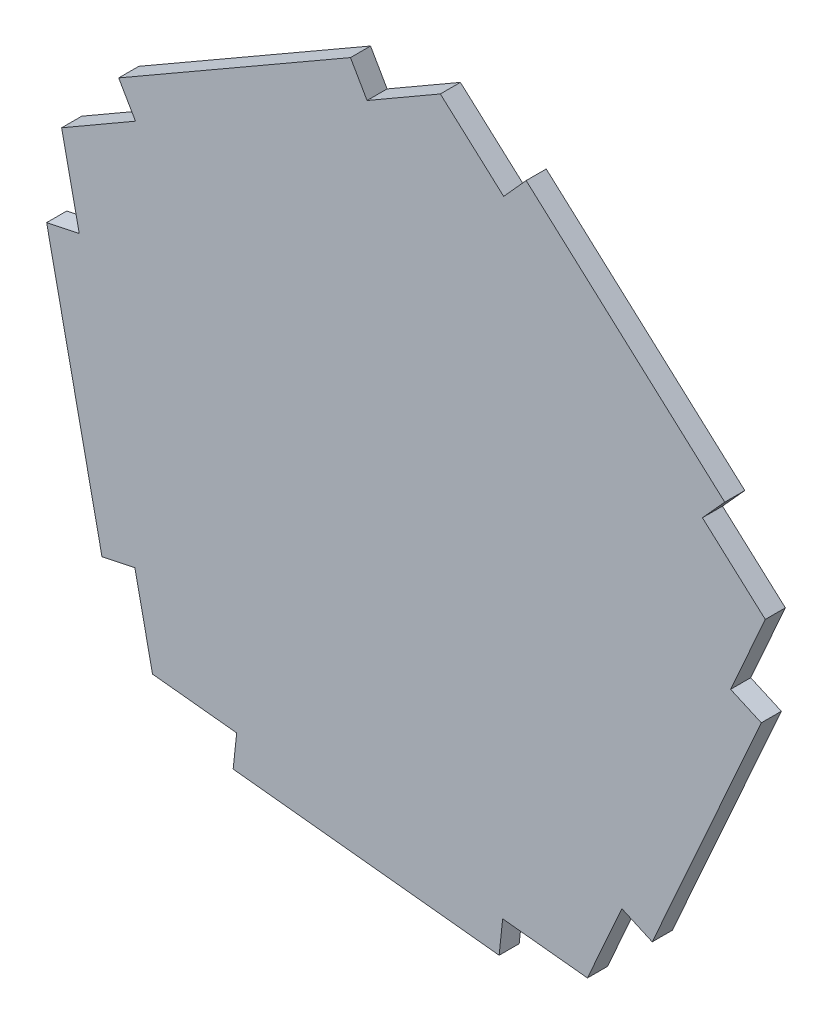
SolidWorks part; units mm, degrees
ref_plane "Front Plane" through (0, 0, 0) normal (0, 0, 1) x (1, 0, 0)
ref_plane "Top Plane" through (0, 0, 0) normal (0, 1, 0) x (1, 0, 0)
ref_plane "Right Plane" through (0, 0, 0) normal (1, 0, 0) x (0, 0, -1)
sketch "Sketch1" plane through (0, 0, 0) normal (0, 0, 1) x (1, 0, 0)
  line L1 (-41.404, -45.8843) -> (30.844, -53.5566)
  line L2 (30.844, -53.5566) -> (60.4667, 12.7845)
  line L3 (60.4667, 12.7845) -> (6.5264, 61.4578)
  line L4 (6.5264, 61.4578) -> (-56.4331, 25.1985)
  line L5 (-56.4331, 25.1985) -> (-41.404, -45.8843)
  circle A0 centre (0, 0) radius 50 construction
extrude "Boss-Extrude1" add sketch "Sketch1" along normal blind 3 contours L4 L5 L1 L2 L3
sketch "Sketch4" plane through (0, 0, 3) normal (0, 0, 1) x (1, 0, 0)
  line L0 (0, 0) -> (30.844, -53.5566) construction
  line L1 (0, 0) -> (-5.28, -49.7204) construction
  line L2 (-41.404, -45.8843) -> (30.844, -53.5566) construction
  line L3 (0, 0) -> (-41.404, -45.8843) construction
  line L4 (0, 0) -> (-48.9186, -10.3429) construction
  line L5 (0, 0) -> (-56.4331, 25.1985) construction
  line L6 (0, 0) -> (-24.9533, 43.3282) construction
  line L7 (0, 0) -> (6.5264, 61.4578) construction
  line L8 (0, 0) -> (33.4965, 37.1212) construction
  line L9 (0, 0) -> (60.4667, 12.7845) construction
  line L10 (0, 0) -> (45.6553, -20.386) construction
  line L11 (-5.28, -49.7204) -> (14.6082, -51.8324) construction
  line L12 (27.8115, -48.171) -> (54.4076, 11.5647)
  line L13 (54.4076, 11.5647) -> (5.8142, 55.3184)
  line L14 (5.8142, 55.3184) -> (-50.8142, 22.6239)
  line L15 (-50.8142, 22.6239) -> (-37.2191, -41.336)
  line L16 (-37.2191, -41.336) -> (27.8115, -48.171)
  line L17 (24.7214, -42.8187) -> (48.3623, 10.2797)
  line L18 (48.3623, 10.2797) -> (5.1682, 49.1719)
  line L19 (5.1682, 49.1719) -> (-45.1682, 20.1102)
  line L20 (-45.1682, 20.1102) -> (-33.0836, -36.7431)
  line L21 (-33.0836, -36.7431) -> (24.7214, -42.8187)
  line L22 (-41.404, -45.8843) -> (30.844, -53.5566) construction
  line L23 (14.6082, -51.8324) -> (15.1331, -46.8384)
  line L24 (15.1331, -46.8384) -> (27.8115, -48.171)
  line L25 (37.5009, -38.6482) -> (32.9179, -36.5959)
  line L26 (37.5009, -38.6482) -> (30.844, -53.5566)
  line L27 (30.844, -53.5566) -> (14.6082, -51.8324)
  line L28 (-44.7814, -29.9103) -> (-39.8696, -28.8663)
  line L29 (-25.1682, -47.6084) -> (-24.6325, -42.6156)
  line L30 (-25.1682, -47.6084) -> (-41.404, -45.8843)
  line L31 (-41.404, -45.8843) -> (-44.7814, -29.9103)
  line L32 (-39.8696, -28.8663) -> (-37.2191, -41.336)
  line L33 (-42.2846, 33.3468) -> (-39.7738, 28.9981)
  line L34 (-53.0557, 9.2245) -> (-48.1417, 10.258)
  line L35 (-53.0557, 9.2245) -> (-56.4331, 25.1985)
  line L36 (-56.4331, 25.1985) -> (-42.2846, 33.3468)
  line L37 (-39.7738, 28.9981) -> (-50.8142, 22.6239)
  line L38 (18.6481, 50.5198) -> (15.288, 46.7881)
  line L39 (-7.6221, 53.3095) -> (-5.1207, 48.9553)
  line L40 (-7.6221, 53.3095) -> (6.5264, 61.4578)
  line L41 (6.5264, 61.4578) -> (18.6481, 50.5198)
  line L42 (15.288, 46.7881) -> (5.8142, 55.3184)
  line L43 (53.8097, -2.1239) -> (49.2224, -0.0815)
  line L44 (48.345, 23.7226) -> (44.9769, 19.9981)
  line L45 (48.345, 23.7226) -> (60.4667, 12.7845)
  line L46 (60.4667, 12.7845) -> (53.8097, -2.1239)
  line L47 (49.2224, -0.0815) -> (54.4076, 11.5647)
  line L48 (32.9179, -36.5959) -> (27.8115, -48.171)
  line L49 (-39.8696, -28.8663) -> (-37.2191, -41.336)
  line L50 (-44.7814, -29.9103) -> (-39.8696, -28.8663)
  line L51 (-41.404, -45.8843) -> (-44.7814, -29.9103)
  line L52 (-25.1682, -47.6084) -> (-41.404, -45.8843)
  line L53 (-25.1682, -47.6084) -> (-24.6325, -42.6156)
  line L54 (-24.6325, -42.6156) -> (-37.2191, -41.336)
  line L55 (-39.7738, 28.9981) -> (-50.8142, 22.6239)
  line L56 (-42.2846, 33.3468) -> (-39.7738, 28.9981)
  line L57 (-56.4331, 25.1985) -> (-42.2846, 33.3468)
  line L58 (-53.0557, 9.2245) -> (-56.4331, 25.1985)
  line L59 (-53.0557, 9.2245) -> (-48.1417, 10.258)
  line L60 (-48.1417, 10.258) -> (-50.8142, 22.6239)
  line L61 (15.288, 46.7881) -> (5.8142, 55.3184)
  line L62 (18.6481, 50.5198) -> (15.288, 46.7881)
  line L63 (6.5264, 61.4578) -> (18.6481, 50.5198)
  line L64 (-7.6221, 53.3095) -> (6.5264, 61.4578)
  line L65 (-7.6221, 53.3095) -> (-5.1207, 48.9553)
  line L66 (-5.1207, 48.9553) -> (5.8142, 55.3184)
  line L67 (49.2224, -0.0815) -> (54.4076, 11.5647)
  line L68 (53.8097, -2.1239) -> (49.2224, -0.0815)
  line L69 (60.4667, 12.7845) -> (53.8097, -2.1239)
  line L70 (48.345, 23.7226) -> (60.4667, 12.7845)
  line L71 (48.345, 23.7226) -> (44.9769, 19.9981)
  line L72 (44.9769, 19.9981) -> (54.4076, 11.5647)
  circle A0 centre (0, 0) radius 45 construction
  circle A1 centre (0, 0) radius 40 construction
  circle A2 centre (0, 0) radius 45 construction
  circle A3 centre (0, 0) radius 45 construction
  circle A4 centre (0, 0) radius 45 construction
  circle A5 centre (0, 0) radius 45 construction
  point P18 (0, 0)
  point P65 (0, 0)
  point P90 (0, 0)
  line M1 (60.4667, 12.7845) -> (6.5264, 61.4578)
  line M2 (6.5264, 61.4578) -> (-56.4331, 25.1985)
  line M3 (-56.4331, 25.1985) -> (-41.404, -45.8843)
  line M4 (-41.404, -45.8843) -> (30.844, -53.5566)
  line M5 (30.844, -53.5566) -> (60.4667, 12.7845)
  dimension "D2" = 20
  dimension "D1" = 5
  dimension "D3" = 5
  dimension "D4" = 5
sketch "Sketch2" plane through (0, 0, 3) normal (0, 0, 1) x (1, 0, 0)
  line L0 (1.6748, 1.8561) -> (0, 0) construction
  line L1 (0, 0) -> (13.9739, -24.2638) construction
  line L2 (2.2828, -1.0193) -> (0, 0) construction
  line L3 (0, 0) -> (30.844, -53.5566) construction
  line L4 (19.4483, -33.7694) -> (14.2489, -36.7638) construction
  line L5 (-1.2477, 2.1664) -> (0, 0) construction
  line L6 (13.9739, -24.2638) -> (14.2489, -36.7638) construction
  line L7 (0, 0) -> (-2.4459, -0.5171) construction
  line L8 (0, 0) -> (-0.264, -2.486) construction
  line L9 (24.6477, -30.775) -> (19.4483, -33.7694) construction
  line L10 (0, 0) -> (27.3944, 5.792) construction
  line L11 (27.3944, 5.792) -> (39.3676, 2.1909) construction
  line L12 (36.8853, 13.9313) -> (38.1264, 8.0611) construction
  line L13 (38.1264, 8.0611) -> (39.3676, 2.1909) construction
  line L14 (0, 0) -> (2.9568, 27.8434) construction
  line L15 (2.9568, 27.8434) -> (10.0816, 38.1178) construction
  line L16 (-1.8513, 39.385) -> (4.1152, 38.7514) construction
  line L17 (4.1152, 38.7514) -> (10.0816, 38.1178) construction
  line L18 (0, 0) -> (-25.567, 11.4162) construction
  line L19 (-25.567, 11.4162) -> (-33.1368, 21.3672) construction
  line L20 (-38.0295, 10.41) -> (-35.5831, 15.8886) construction
  line L21 (-35.5831, 15.8886) -> (-33.1368, 21.3672) construction
  line L22 (0, 0) -> (-18.7581, -20.7879) construction
  line L23 (-18.7581, -20.7879) -> (-30.5613, -24.9121) construction
  line L24 (-21.6522, -32.9513) -> (-26.1067, -28.9317) construction
  line L25 (-26.1067, -28.9317) -> (-30.5613, -24.9121) construction
  circle A6 centre (0, 0) radius 2.5
  circle A7 centre (13.9739, -24.2638) radius 2.5
  circle A12 centre (14.2489, -36.7638) radius 2.5
  circle A13 centre (24.6477, -30.775) radius 2.5
  circle A22 centre (27.3944, 5.792) radius 2.5
  circle A23 centre (39.3676, 2.1909) radius 2.5
  circle A24 centre (36.8853, 13.9313) radius 2.5
  circle A25 centre (2.9568, 27.8434) radius 2.5
  circle A26 centre (10.0816, 38.1178) radius 2.5
  circle A27 centre (-1.8513, 39.385) radius 2.5
  circle A28 centre (-25.567, 11.4162) radius 2.5
  circle A29 centre (-33.1368, 21.3672) radius 2.5
  circle A30 centre (-38.0295, 10.41) radius 2.5
  circle A31 centre (-18.7581, -20.7879) radius 2.5
  circle A32 centre (-30.5613, -24.9121) radius 2.5
  circle A33 centre (-21.6522, -32.9513) radius 2.5
  point P21 (0, 0)
  point P45 (-0.3503, 0.9716)
  point P50 (0, 0)
  dimension "D1" = 28
  dimension "D2" = 6
  dimension "D3" = 12.5
  dimension "D4" = 5
extrude "Cut-Extrude3" cut sketch "Sketch4" against normal blind 10 contours L34 L15 L14 L33 M3 M2 | L39 L14 L13 L38 M2 M1 | L44 L13 L12 L43 M1 M5 | L25 L12 L16 L23 M5 M4 | L29 L16 L15 L28 M4 M3
